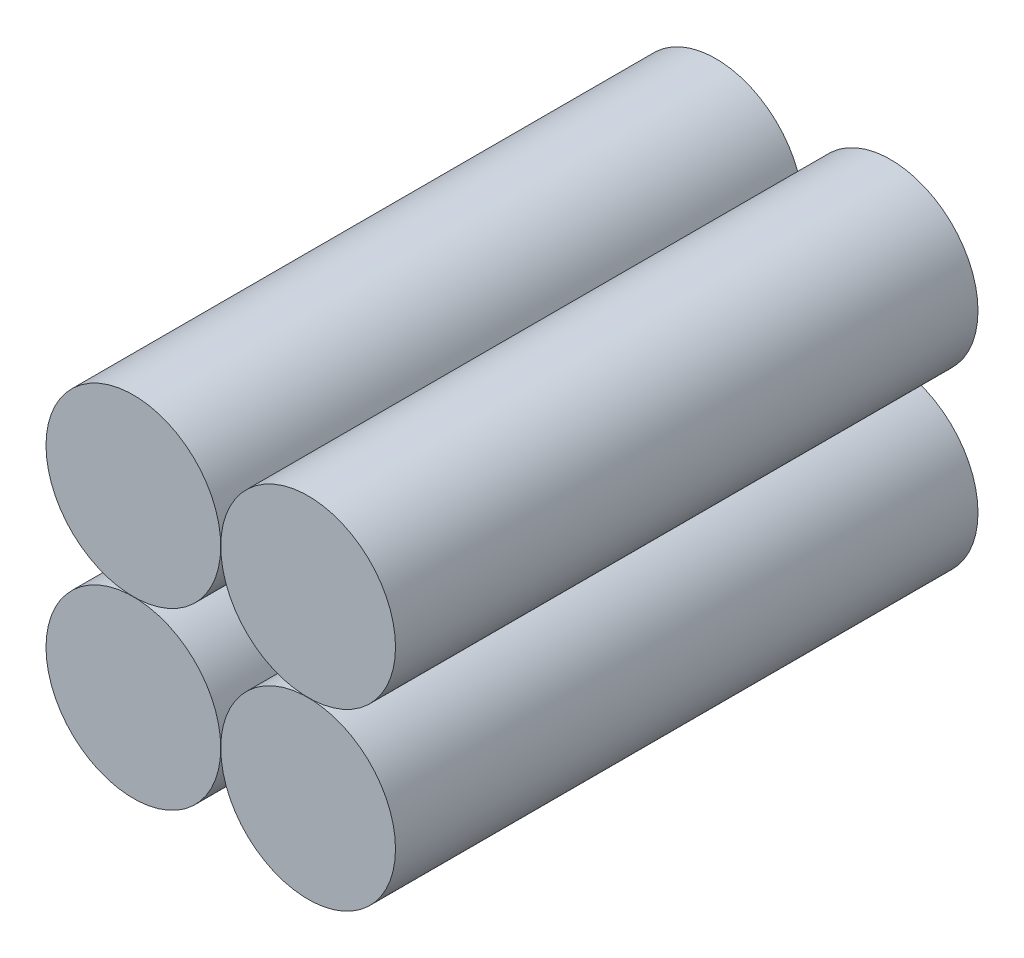
SolidWorks part; units mm, degrees
material "Battaty"
ref_plane "Front Plane" through (0, 0, 0) normal (0, 0, 1) x (1, 0, 0)
ref_plane "Top Plane" through (0, 0, 0) normal (0, 1, 0) x (1, 0, 0)
ref_plane "Right Plane" through (0, 0, 0) normal (1, 0, 0) x (0, 0, -1)
sketch "Sketch1" plane through (0, 0, 0) normal (0, 0, 1) x (1, 0, 0)
  line L1 (10.5, 10.5) -> (-10.5, 10.5) construction
  line L2 (10.5, 10.5) -> (10.5, -10.5) construction
  line L3 (10.5, -10.5) -> (-10.5, -10.5) construction
  line L4 (-10.5, 10.5) -> (-10.5, -10.5) construction
  line L5 (10.5, 10.5) -> (-10.5, -10.5) construction
  line L6 (10.5, -10.5) -> (-10.5, 10.5) construction
  circle A0 centre (-10.5, 10.5) radius 10.5
  circle A1 centre (-10.5, -10.5) radius 10.5
  circle A2 centre (10.5, -10.5) radius 10.5
  circle A3 centre (10.5, 10.5) radius 10.5
  point P0 (0, 0)
  dimension "D1" = 21
extrude "Boss-Extrude1" add sketch "Sketch1" along normal blind 70 contours A0 | A3 | A1 | A2
